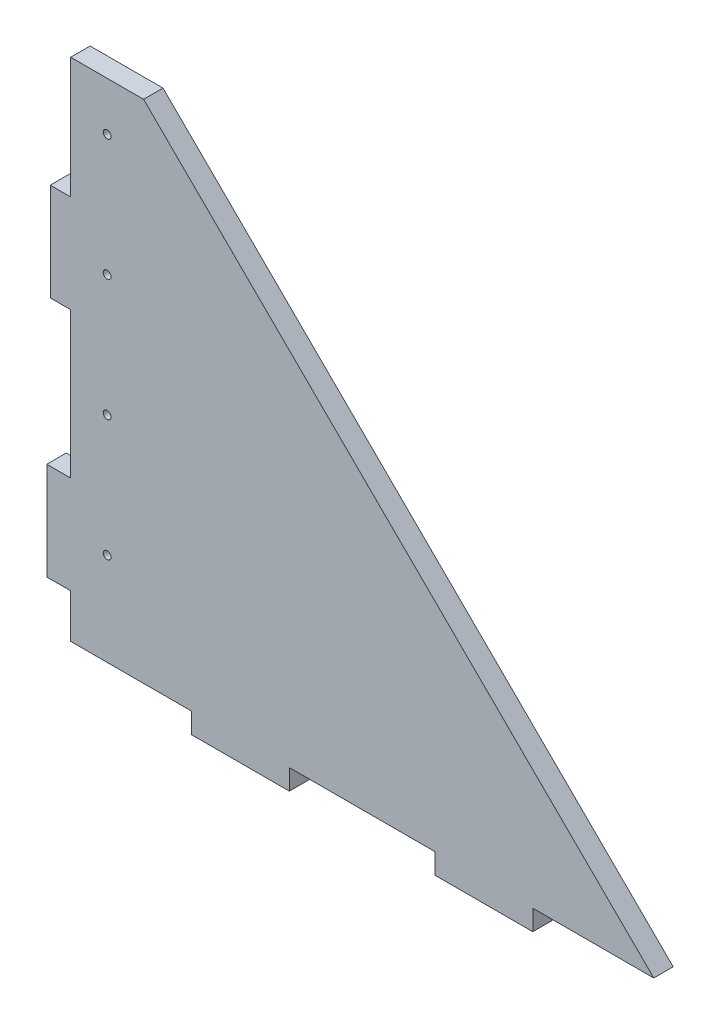
SolidWorks part; units mm, degrees
ref_plane "Front Plane" through (0, 0, 0) normal (0, 0, 1) x (1, 0, 0)
ref_plane "Top Plane" through (0, 0, 0) normal (0, 1, 0) x (1, 0, 0)
ref_plane "Right Plane" through (0, 0, 0) normal (1, 0, 0) x (0, 0, -1)
sketch "Sketch1" plane through (0, 0, 0) normal (0, 0, 1) x (1, 0, 0)
  line L0 (0, 0) -> (0, 9.01)
  line L1 (0, 0) -> (24.9, 0)
  line L3 (-4.9132, 9.01) -> (-4.9132, 29.11)
  line L4 (-4.9132, 9.01) -> (0, 9.01)
  line L5 (95.1, 0) -> (120, 0)
  line L6 (-4.9132, 29.11) -> (0, 29.11)
  line L7 (0, 29.11) -> (0, 59.11)
  line L8 (0, 59.11) -> (-4.2, 59.11)
  line L9 (-4.2, 59.11) -> (-4.2, 79.21)
  line L10 (0, 79.21) -> (-4.2, 79.21)
  line L11 (0, 79.21) -> (0, 104.11)
  line L12 (95.1, 0) -> (95.1, -4.2)
  line L13 (75, -4.2) -> (95.1, -4.2)
  line L14 (75, 0) -> (75, -4.2)
  line L15 (45, 0) -> (75, 0)
  line L16 (45, -4.2) -> (45, 0)
  line L17 (0, 104.11) -> (15, 104.11)
  line L18 (24.9, -4.2) -> (24.9, 0)
  line L19 (24.9, -4.2) -> (45, -4.2)
  line L20 (15, 104.11) -> (120, 0)
  dimension "D1" = 104.11
  dimension "D2" = 30
  dimension "D3" = 20.1
  dimension "D4" = 4.2
  dimension "D5" = 9.01
  dimension "D6" = 20.1
  dimension "D7" = 4.2
  dimension "D8" = 30
  dimension "D9" = 24.9
  dimension "D10" = 15
  dimension "D11" = 24.9
extrude "Boss-Extrude1" add sketch "Sketch1" along normal blind 4
sketch "Sketch2" plane through (0, 0, 4) normal (0, 0, 1) x (1, 0, 0)
  line L0 (7.5, 104.11) -> (7.5, 0) construction
  line L1 (15, 104.11) -> (0, 104.11) construction
  line L2 (0, 0) -> (24.9, 0) construction
  circle A0 centre (7.5, 94.11) radius 0.8
  dimension "D1" = 1.6
  dimension "D2" = 10
extrude "Cut-Extrude1" cut sketch "Sketch2" against normal blind 4
pattern_linear "LPattern1" count 4 spacing 25 along (0, -1, 0) of "Cut-Extrude1"
equation "\"obwidth\"=15"
equation "\"obchannel\"=3.2"
equation "\"bracewidth\"=120.000000"
equation "\"sheetthickness\"=4"
equation "\"slotwidth\"=\"sheetthickness\"+0.2"
equation "\"slotlength\"=20.1"
